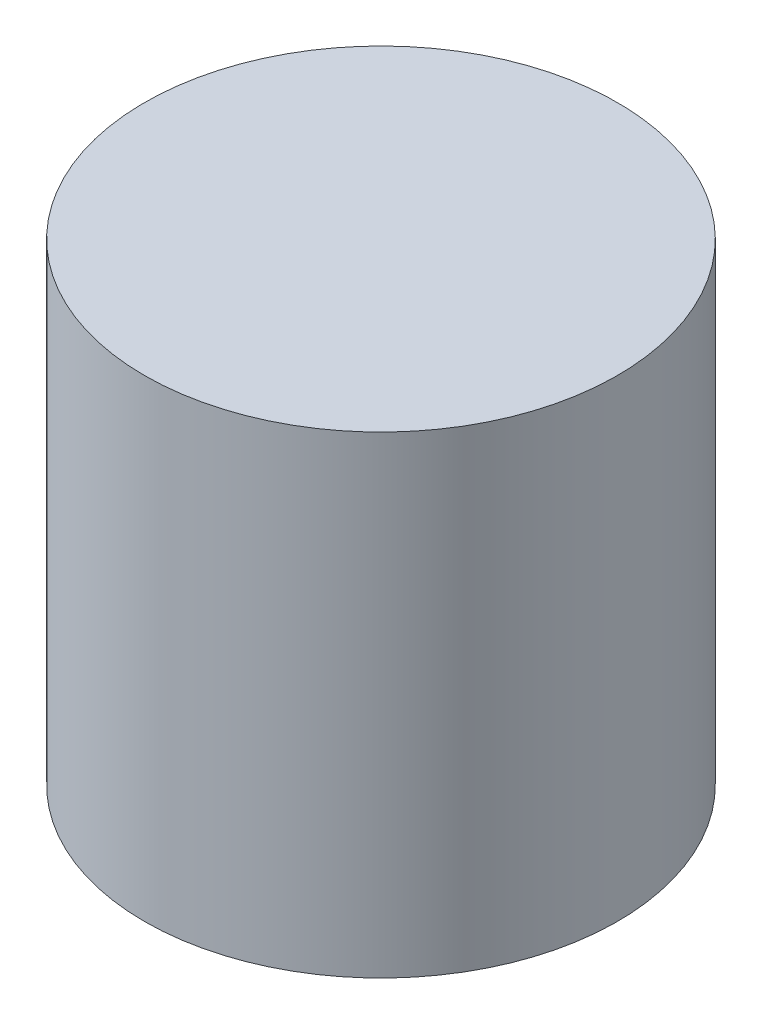
SolidWorks part; units mm, degrees
ref_plane "Front Plane" through (0, 0, 0) normal (0, 0, 1) x (1, 0, 0)
ref_plane "Top Plane" through (0, 0, 0) normal (0, 1, 0) x (1, 0, 0)
ref_plane "Right Plane" through (0, 0, 0) normal (1, 0, 0) x (0, 0, -1)
sketch "Sketch2" plane through (0, 0, 0) normal (0, 1, 0) x (1, 0, 0)
  circle A0 centre (0, 0) radius 25.4
extrude "Boss-Extrude1" add sketch "Sketch2" along normal blind 50.8
ref_point "Point2"
